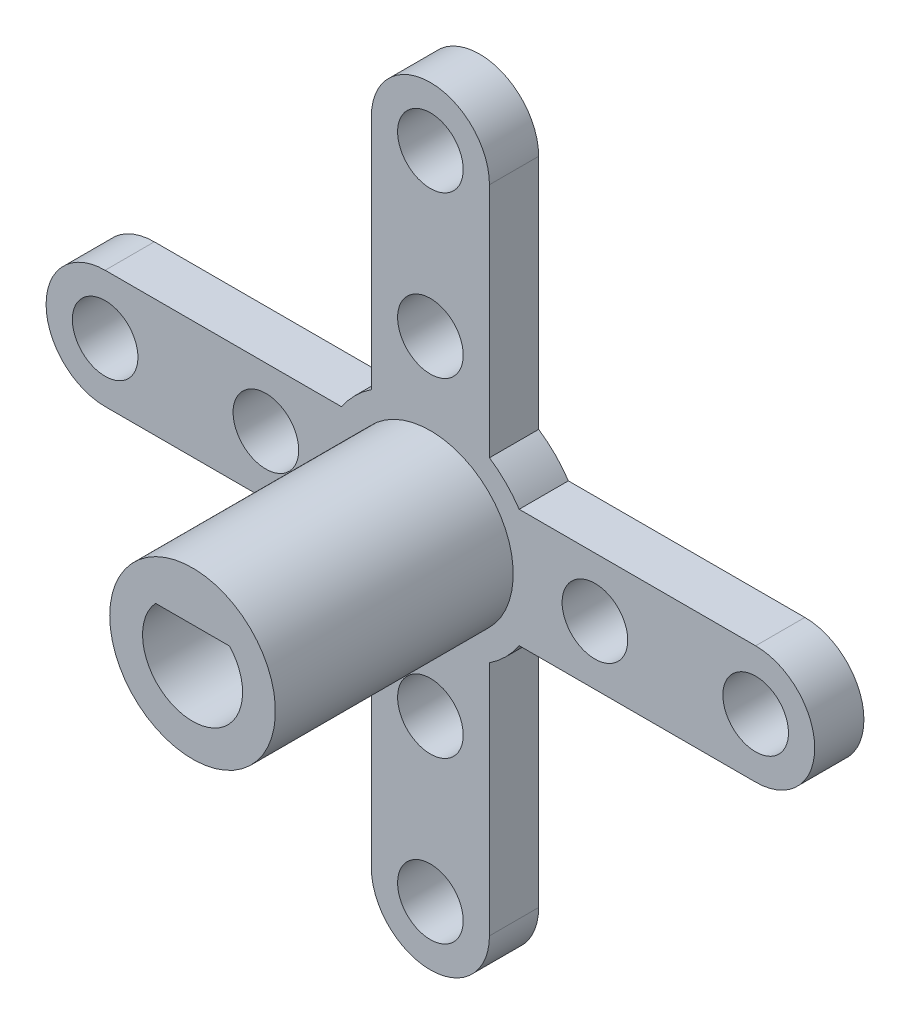
SolidWorks part; units mm, degrees
ref_plane "Přední rovina" through (0, 0, 0) normal (0, 0, 1) x (1, 0, 0)
ref_plane "Horní rovina" through (0, 0, 0) normal (0, 1, 0) x (1, 0, 0)
ref_plane "Pravá rovina" through (0, 0, 0) normal (1, 0, 0) x (0, 0, -1)
sketch "Sketch1" plane through (0, 0, 0) normal (0, 0, 1) x (1, 0, 0)
  line L0 (0, 9.915) -> (0, -9.915) construction
  line L1 (1.8, 9.915) -> (1.8, -9.915)
  line L2 (-1.8, 9.915) -> (-1.8, -9.915)
  line L3 (-9.3, 0) -> (9.3, 0) construction
  line L4 (-9.3, 1.8) -> (9.3, 1.8)
  line L5 (-9.3, -1.8) -> (9.3, -1.8)
  arc A0 (1.8, 9.915) -> (-1.8, 9.915) centre (0, 9.915) ccw
  arc A1 (-1.8, -9.915) -> (1.8, -9.915) centre (0, -9.915) ccw
  arc A2 (-9.3, 1.8) -> (-9.3, -1.8) centre (-9.3, 0) ccw
  arc A3 (9.3, -1.8) -> (9.3, 1.8) centre (9.3, 0) ccw
  circle A4 centre (0, 0) radius 1
  circle A7 centre (0, 5.015) radius 1
  circle A8 centre (0, 9.915) radius 1
  circle A9 centre (0, 0) radius 3.25
  point P3 (0, 0)
  point P10 (0, 0)
  dimension "D3" = 2
  dimension "D4" = 1.8
  dimension "D5" = 1.8
  dimension "D6" = 2
  dimension "D7" = 2
  dimension "D10" = 6.5
  dimension "D1" = 19.83
  dimension "D2" = 18.6
  dimension "D8" = 4.9
extrude "Boss-Extrude1" add sketch "Sketch1" along normal blind 1.5 contours L4 A9 L5 L2 | L5 A9 L2 | L2 A9 L1 L5 | L1 A9 L5 | L5 A9 L4 L1 | L4 A9 L1 | L1 A9 L2 L4 | L2 A9 L4 | L2 L5 L1 L4 A4 | A9 L1 A0 L2 A8 A7
pattern_circular "CirPattern1" count 4 over 360 about axis through (0, 0, 0) along (0, 0, 1) of "Boss-Extrude1"
sketch "Sketch2" plane through (0, 0, 0) normal (0, 0, -1) x (-1, 0, 0)
  line L1 (2.05, 1.7571) -> (-2.05, 1.7571)
  line L2 (2.05, -1.7571) -> (-2.05, -1.7571)
  circle A0 centre (0, 0) radius 2.7
  dimension "D1" = 5.4
  dimension "D2" = 4.1
  dimension "D3" = 4.1
extrude "Boss-Extrude2" [suppressed] add sketch "Sketch2" along normal blind 2
sketch "Sketch3" plane through (0, 0, 1.5) normal (0, 0, 1) x (1, 0, 0)
  line L0 (-1.1292, 1.025) -> (1.1292, 1.025)
  line L1 (0, -1.525) -> (0, 0) construction
  circle A0 centre (0, 0) radius 2.525
  circle A1 centre (0, 0) radius 1.525
  dimension "D1" = 1
  dimension "D2" = 3.05
  dimension "D3" = 2.55
extrude "Boss-Extrude3" add sketch "Sketch3" along normal blind 7.25
